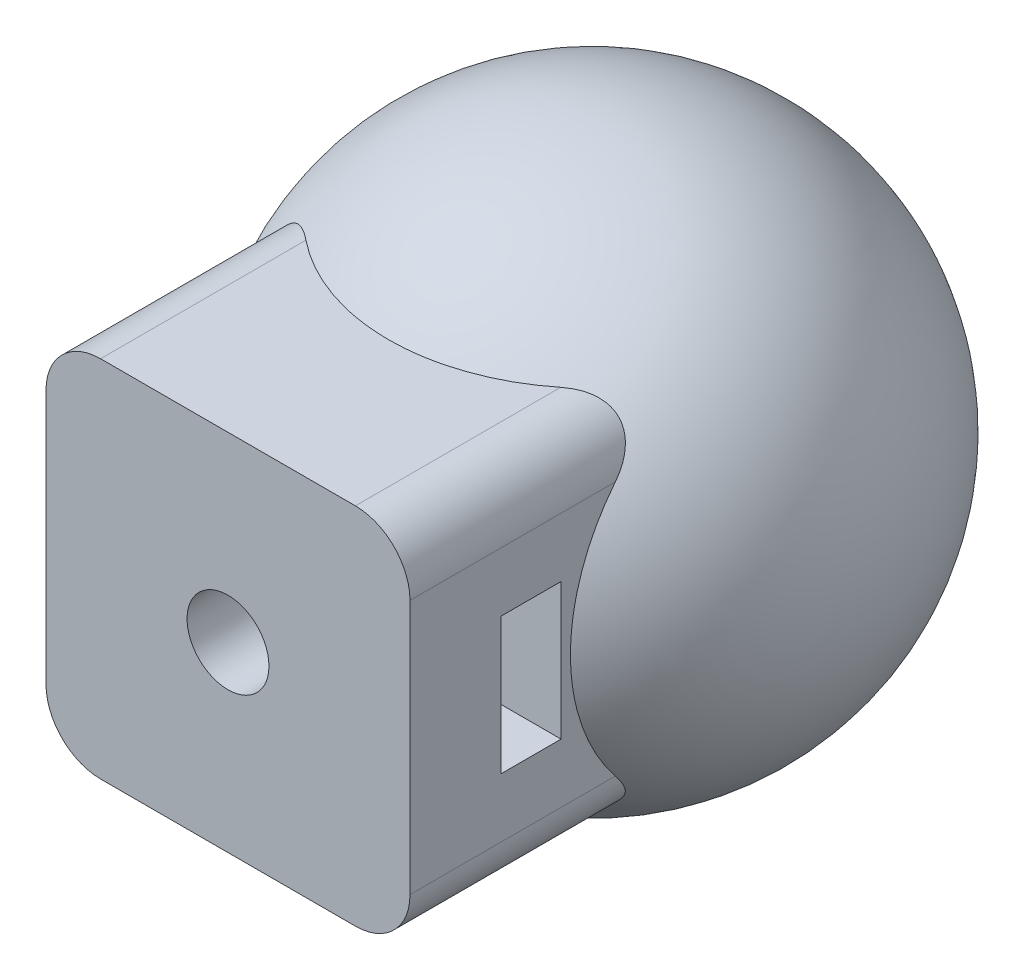
SolidWorks part; units mm, degrees
ref_plane "Front Plane" through (0, 0, 0) normal (0, 0, 1) x (1, 0, 0)
ref_plane "Top Plane" through (0, 0, 0) normal (0, 1, 0) x (1, 0, 0)
ref_plane "Right Plane" through (0, 0, 0) normal (1, 0, 0) x (0, 0, -1)
sketch "Sketch1" plane through (0, 0, 0) normal (0, 1, 0) x (1, 0, 0)
  line L0 (0, 15) -> (0, -15) construction
  line L1 (0, 15) -> (0, -15)
  arc A0 (0, 15) -> (0, -15) centre (0, 0) ccw
  dimension "D1" = 30
revolve "Revolve1" add sketch "Sketch1" angle 360 about L0
sketch "Sketch2" plane through (0, 0, 0) normal (0, 0, 1) x (1, 0, 0)
  line L1 (-10, 10) -> (10, 10)
  line L2 (-10, 10) -> (-10, -10)
  line L3 (-10, -10) -> (10, -10)
  line L4 (10, 10) -> (10, -10)
  line L5 (-10, 10) -> (10, -10) construction
  line L6 (-10, -10) -> (10, 10) construction
  point P0 (0, 0)
  dimension "D1" = 20
  dimension "D2" = 20
extrude "Boss-Extrude1" add sketch "Sketch2" along normal blind 20
sketch "Sketch3" plane through (0, 0, 20) normal (0, 0, 1) x (1, 0, 0)
  circle A0 centre (0, 0) radius 2.25
  dimension "D1" = 4.5
extrude "Cut-Extrude1" cut sketch "Sketch3" against normal blind 20
ref_plane "Plane1" through (0, 0, 15) normal (0, 0, 1) x (1, 0, 0)
sketch "Sketch4" plane through (0, 0, 15) normal (0, 0, 1) x (1, 0, 0)
  line L0 (2.1651, 3.75) -> (10, 3.75)
  line L2 (2.1651, 3.75) -> (-2.1651, 3.75)
  line L3 (-2.1651, 3.75) -> (-4.3301, 0)
  line L4 (-4.3301, 0) -> (-2.1651, -3.75)
  line L5 (-2.1651, -3.75) -> (2.1651, -3.75)
  line L7 (10, -10) -> (10, 10) construction
  line L8 (2.1651, -3.75) -> (10, -3.75)
  line L9 (10, -10) -> (10, 10) construction
  line L10 (10, -3.75) -> (10, 3.75)
  line L12 (3.2476, -1.875) -> (4.3301, 0) [skipped]
  line L13 (4.3301, 0) -> (3.2476, 1.875) [skipped]
  circle A0 centre (0, 0) radius 3.75 construction
extrude "Cut-Extrude2" cut sketch "Sketch4" against normal blind 3.3 contours L5 L4 L3 L2 L0 L10 L8
fillet "Fillet1" radius 3 4 edges at (-10, -10, 12.5) (10, -10, 12.5) (10, 10, 12.5) (-10, 10, 12.5)
